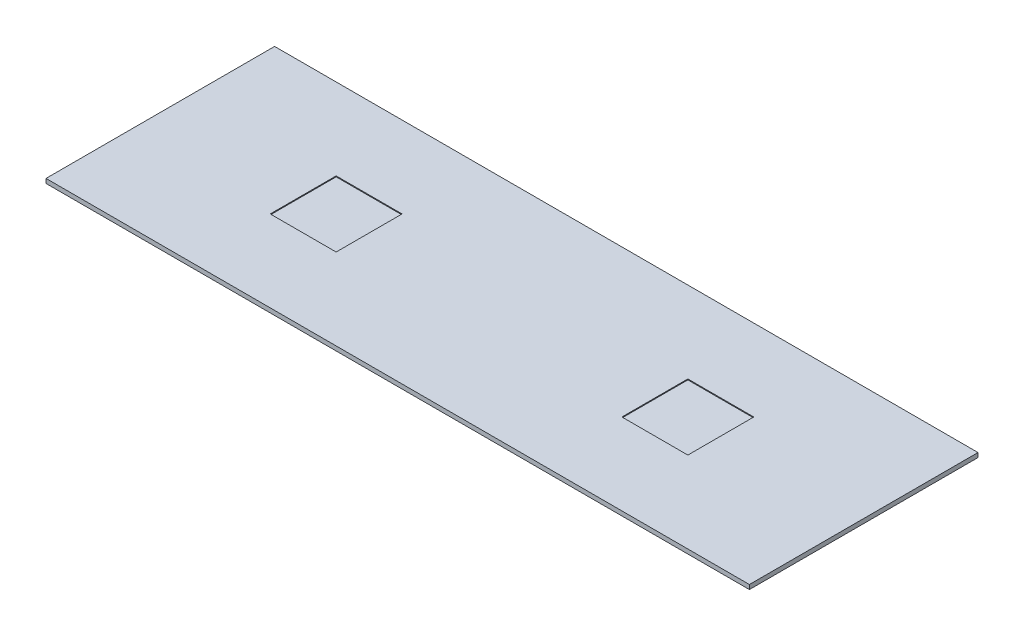
SolidWorks part; units mm, degrees
ref_plane "Front Plane" through (0, 0, 0) normal (0, 0, 1) x (1, 0, 0)
ref_plane "Top Plane" through (0, 0, 0) normal (0, 1, 0) x (1, 0, 0)
ref_plane "Right Plane" through (0, 0, 0) normal (1, 0, 0) x (0, 0, -1)
sketch "Sketch1" plane through (0, 0, 0) normal (0, 1, 0) x (1, 0, 0)
  line L1 (4000, -1300) -> (-4000, -1300)
  line L2 (4000, -1300) -> (4000, 1300)
  line L3 (4000, 1300) -> (-4000, 1300)
  line L4 (-4000, -1300) -> (-4000, 1300)
  line L5 (4000, -1300) -> (-4000, 1300) construction
  line L6 (4000, 1300) -> (-4000, -1300) construction
  point P0 (0, 0)
  dimension "D1" = 8000
  dimension "D2" = 2600
extrude "Boss-Extrude1" add sketch "Sketch1" along normal blind 50
sketch "Sketch2" plane through (0, 50, 0) normal (0, 1, 0) x (1, 0, 0)
  line L0 (-4000, 0) -> (4000, 0) construction
  line L1 (-4000, 1300) -> (-4000, -1300) construction
  line L2 (4000, -1300) -> (4000, 1300) construction
  line L3 (0, 1300) -> (0, -1300) construction
  line L4 (4000, 1300) -> (-4000, 1300) construction
  line L5 (-4000, -1300) -> (4000, -1300) construction
  line L6 (-2000, 1300) -> (-2000, -1300) construction
  line L7 (2000, 1300) -> (2000, -1300) construction
  line L9 (-1625, -375) -> (-2375, -375)
  line L10 (-1625, -375) -> (-1625, 375)
  line L11 (-1625, 375) -> (-2375, 375)
  line L12 (-2375, -375) -> (-2375, 375)
  line L13 (-1625, -375) -> (-2375, 375) construction
  line L14 (-1625, 375) -> (-2375, -375) construction
  line L15 (2375, -375) -> (1625, -375)
  line L16 (2375, -375) -> (2375, 375)
  line L17 (2375, 375) -> (1625, 375)
  line L18 (1625, -375) -> (1625, 375)
  line L19 (2375, -375) -> (1625, 375) construction
  line L20 (2375, 375) -> (1625, -375) construction
  point P16 (-2000, 0)
  point P21 (2000, 0)
  dimension "D1" = 4000
  dimension "D2" = 2000
  dimension "D3" = 2000
  dimension "D4" = 750
  dimension "D5" = 750
  dimension "D6" = 750
  dimension "D7" = 750
extrude "Cut-Extrude1" cut sketch "Sketch2" against normal blind 10
